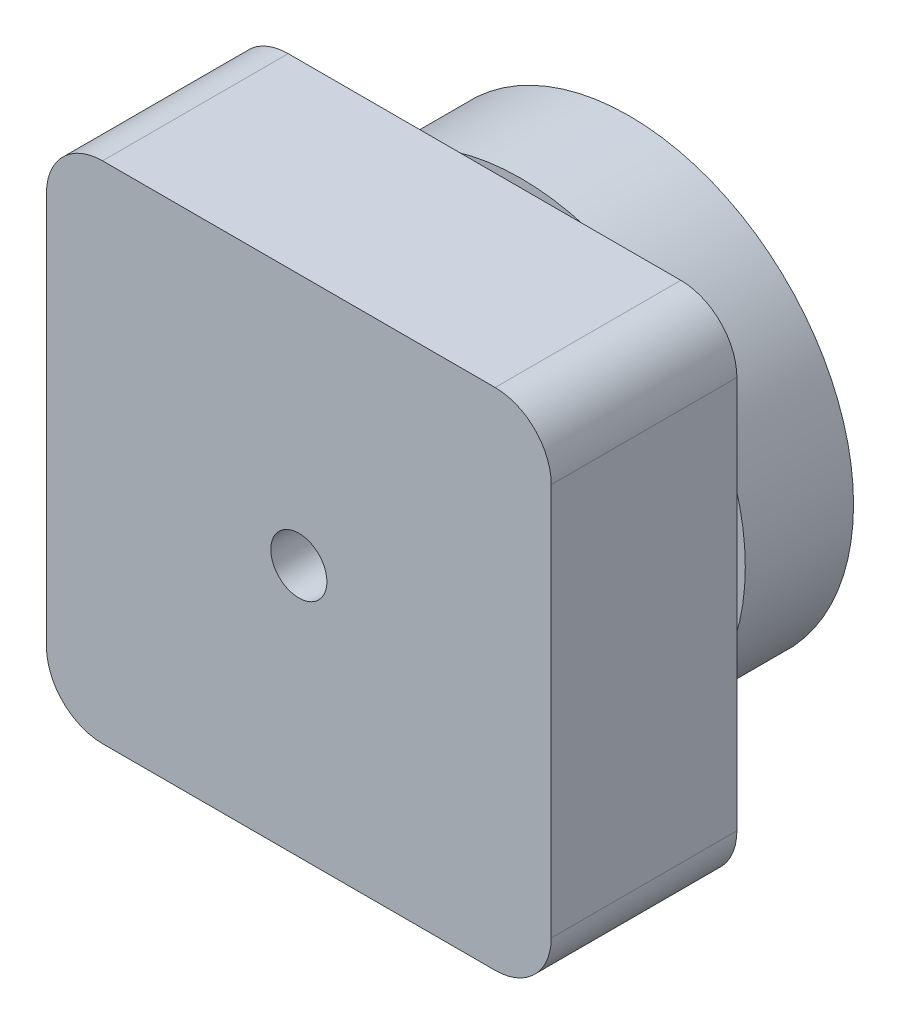
SolidWorks part; units mm, degrees
ref_plane "Front Plane" through (0, 0, 0) normal (0, 0, 1) x (1, 0, 0)
ref_plane "Top Plane" through (0, 0, 0) normal (0, 1, 0) x (1, 0, 0)
ref_plane "Right Plane" through (0, 0, 0) normal (1, 0, 0) x (0, 0, -1)
ref_plane "Plane1" through (0, 0, 0) normal (0, -1, 0) x (1, 0, 0)
sketch "Sketch1" plane through (0, 0, 0) normal (0, -1, 0) x (1, 0, 0)
  line L0 (40, -6.5) -> (0, -6.5)
  line L1 (0, -6.5) -> (0, -25.8)
  line L2 (0, -25.8) -> (40, -25.8)
  line L3 (40, -25.8) -> (40, -6.5)
  line L4 (0, -6.5) -> (0, -25.8) construction
revolve "Revolve1" add sketch "Sketch1" angle 360 about L4
sketch "Sketch2" plane through (0, 0, -6.5) normal (0, 0, 1) x (1, 0, 0)
  circle A0 centre (0, 0) radius 20
extrude "Boss-Extrude1" add sketch "Sketch2" along normal blind 6.5
hole_wizard "CBORE for M8 Hex Head Bolt1" positions "Sketch4" profile "Sketch3" counterbore size "M8" standard "ANSI Metric"
sketch "Sketch4" plane through (0, 0, 0) normal (0, 0, 1) x (1, 0, 0)
  point P0 (0, 0)
sketch "Sketch3" plane through (0, 0, 0) normal (1, 0, 0) x (0, -1, 0)
  line L0 (0, 0) -> (0, 25.8)
  line L1 (0, 25.8) -> (5, 25.8)
  line L3 (5, 25.8) -> (5, 4)
  line L4 (5, 4) -> (10, 4)
  line L5 (10, 4) -> (10, 0)
  line L7 (10, 0) -> (0, 0)
  line L11 (0, -6.35) -> (0, 107.95) construction
  dimension "Thru Hole Dia." = 10
  dimension "Thru Hole Depth" = 25.8
  dimension "C'Bore Dia." = 20
  dimension "C'Bore Depth" = 4
hole_wizard "Ø5.0 (5) Diameter Hole1" positions "Sketch6" profile "Sketch5" hole size "Ø5.0" standard "ANSI Metric"
sketch "Sketch6" plane through (0, 0, 0) normal (0, 0, 1) x (1, 0, 0)
  point P0 (-15.75, 0)
  point P1 (-11.1369, 11.1369)
  point P2 (-11.1369, -11.1369)
  point P3 (11.1369, -11.1369)
  point P4 (11.1369, 11.1369)
sketch "Sketch5" plane through (-15.75, 0, 0) normal (1, 0, 0) x (0, -1, 0)
  line L0 (0, 0) -> (0, 8)
  line L1 (0, 8) -> (2.5, 8)
  line L2 (2.5, 8) -> (2.5, 0)
  line L5 (2.5, 0) -> (0, 0)
  line L10 (0, 8) -> (-2.5, 8) construction
  line L11 (0, -6.35) -> (0, 107.95) construction
  dimension "Hole Dia." = 5
  dimension "Hole Depth" = 8
  dimension "Drill Angle" = 180
sketch "Sketch7" plane through (0, 0, 0) normal (0, 0, 1) x (1, 0, 0)
  line L1 (-45, -45) -> (45, -45)
  line L2 (-45, -45) -> (-45, 45)
  line L3 (-45, 45) -> (45, 45)
  line L4 (45, -45) -> (45, 45)
  line L5 (-45, -45) -> (45, 45) construction
  line L6 (-45, 45) -> (45, -45) construction
  circle A0 centre (0, 0) radius 5
  point P0 (0, 0)
  dimension "D1" = 90
extrude "Boss-Extrude2" add sketch "Sketch7" along normal blind 33.1
fillet "Fillet1" radius 10 4 edges at (-45, -45, 16.55) (45, -45, 16.55) (45, 45, 16.55) (-45, 45, 16.55)
